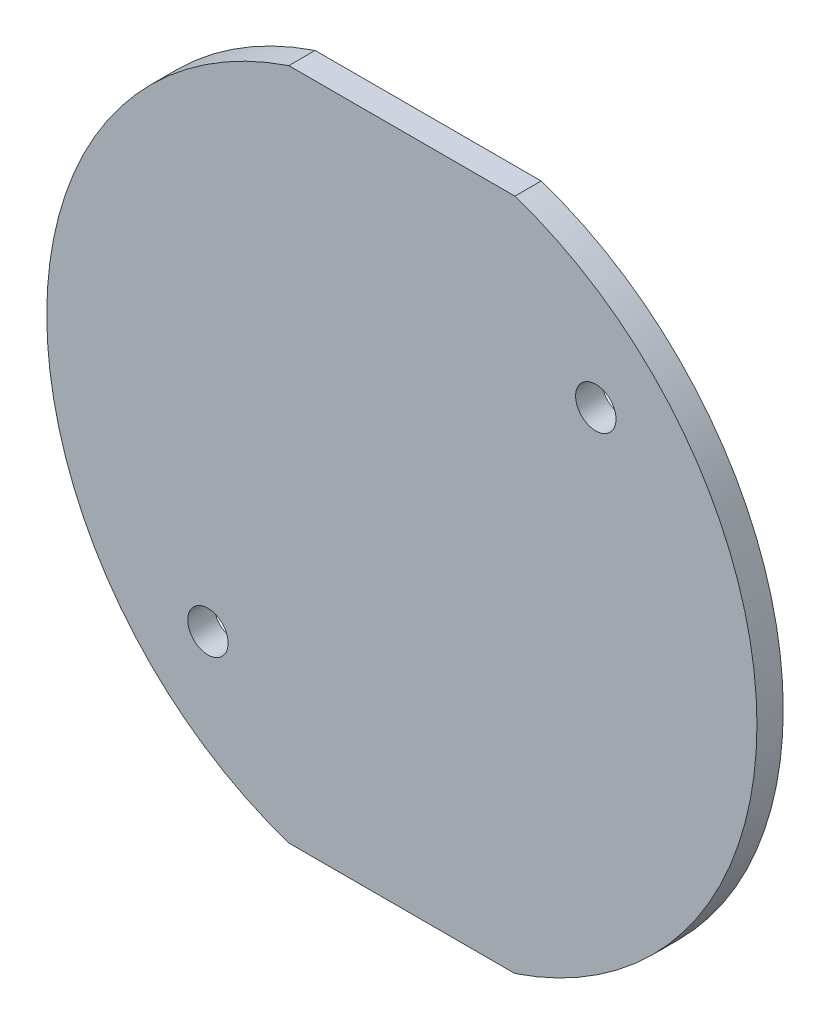
SolidWorks part; units mm, degrees
material "E-Glass Fiber"
ref_plane "Front Plane" through (0, 0, 0) normal (0, 0, 1) x (1, 0, 0)
ref_plane "Top Plane" through (0, 0, 0) normal (0, 1, 0) x (1, 0, 0)
ref_plane "Right Plane" through (0, 0, 0) normal (1, 0, 0) x (0, 0, -1)
sketch "Sketch1" plane through (0, 0, 0) normal (0, 0, 1) x (1, 0, 0)
  circle A0 centre (0, 0) radius 21.971
  dimension "D1" = 43.942
extrude "Boss-Extrude1" add sketch "Sketch1" along normal blind 1.6256
sketch "Sketch2" plane through (0, 0, 1.6256) normal (0, 0, 1) x (1, 0, 0)
  line L1 (-12, 12) -> (12, 12) construction
  line L2 (-12, 12) -> (-12, -12) construction
  line L3 (-12, -12) -> (12, -12) construction
  line L4 (12, 12) -> (12, -12) construction
  line L5 (-12, 12) -> (12, -12) construction
  line L6 (-12, -12) -> (12, 12) construction
  circle A0 centre (12, 12) radius 1.25
  circle A1 centre (-12, -12) radius 1.25
  point P0 (0, 0)
  dimension "D2" = 2.5
  dimension "D1" = 24
extrude "Cut-Extrude1" cut sketch "Sketch2" against normal through all
sketch "Sketch3" plane through (0, 0, 0) normal (0, 0, -1) x (-1, 0, 0)
  line L0 (-6.9942, 20.828) -> (6.9942, 20.828)
  line L1 (-6.9942, 20.828) -> (-6.9942, 26.025)
  line L2 (-6.9942, 26.025) -> (6.9942, 26.025)
  line L3 (6.9942, 26.025) -> (6.9942, 20.828)
  line L4 (-21.971, 0) -> (21.971, 0) construction
  line L5 (6.9942, -26.025) -> (6.9942, -20.828)
  line L6 (-6.9942, -26.025) -> (6.9942, -26.025)
  line L7 (-6.9942, -20.828) -> (-6.9942, -26.025)
  line L8 (-6.9942, -20.828) -> (6.9942, -20.828)
  circle A0 centre (0, 0) radius 21.971 construction
  point P0 (0, 21.971)
  point P14 (0, -21.971)
  dimension "D1" = 1.143
extrude "Cut-Extrude2" cut sketch "Sketch3" against normal through all
